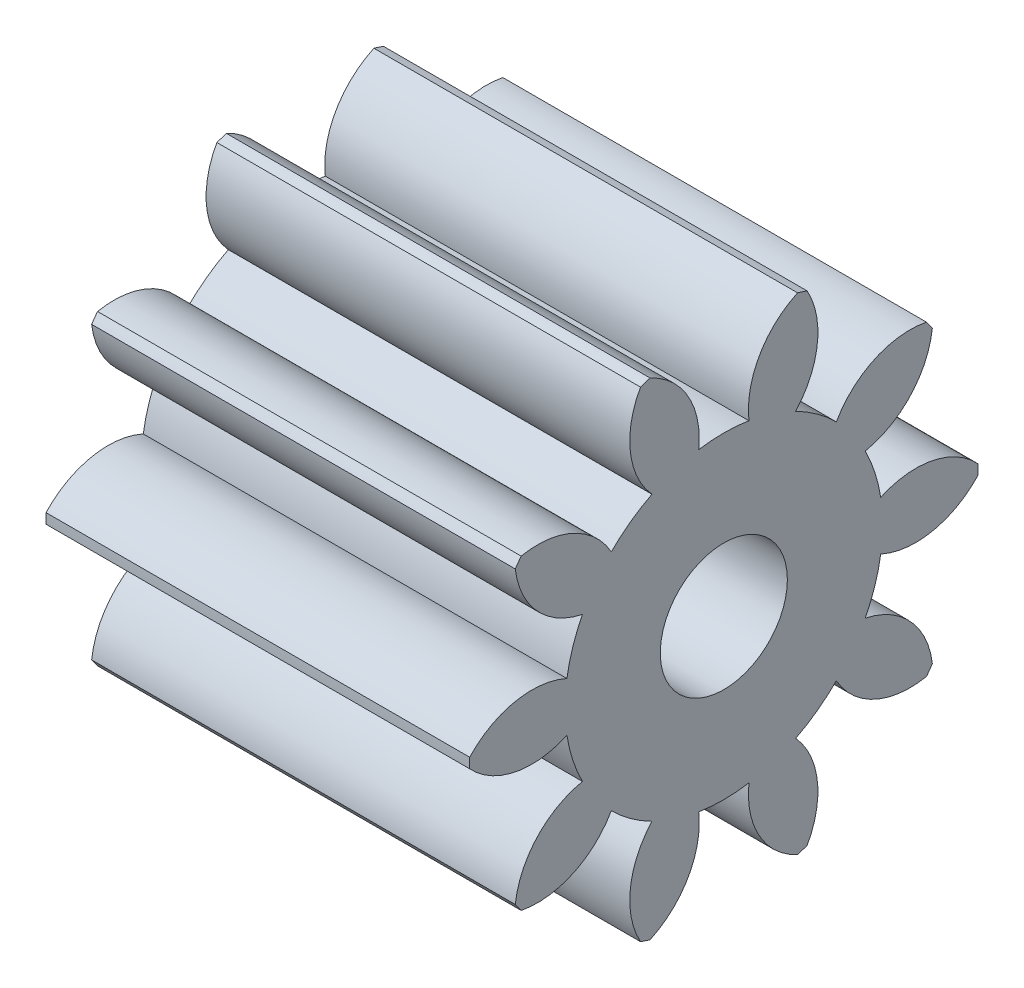
SolidWorks part; units mm, degrees
ref_plane "Plane1" through (0, 0, 0) normal (0, 0, 1) x (1, 0, 0)
ref_plane "Plane2" through (0, 0, 0) normal (0, 1, 0) x (1, 0, 0)
ref_plane "Plane3" through (0, 0, 0) normal (1, 0, 0) x (0, 0, -1)
sketch "HoldingSke" plane through (0, 0, 0) normal (0, 1, 0) x (1, 0, 0)
  line L0 (0, 0) -> (0.9848, -0.1736)
  line L1 (-15, 0) -> (100, 0) construction
  line L2 (0, 0) -> (-2.1039, 2.3779)
  line L3 (0, 0) -> (-11.863, 4.5341)
  line L4 (0, 0) -> (8.5048, 1.4996)
  line L5 (0, 0) -> (-46.8476, -17.4728)
  line L6 (0, 0) -> (-9.9476, -6.7116)
  line L7 (-2.1039, 2.3779) -> (8.6586, 51.2059)
  line L8 (-76.2, 54.61) -> (-76.1, 54.61)
  line L9 (-71.009, 38.7566) -> (-53.1078, 45.2721)
  line L10 (-76.2, 71.12) -> (104.1128, 71.12)
  line L11 (0, 0) -> (-12, 0)
  line L12 (-76.2, 101.6) -> (-76.162, 101.6)
  line L13 (24.9733, 27.94) -> (52.9518, 28.4284)
  line L14 (24.9733, 27.94) -> (24.9743, 27.94)
  line L15 (24.9733, 27.94) -> (100.4006, 29.5858)
  line L16 (-63.627, -1) -> (-12.827, -1)
  circle A0 centre (0, 0) radius 0.4
  circle A1 centre (0, 0) radius 3.749
  circle A2 centre (0, 0) radius 37.5
  circle A3 centre (0, 0) radius 0.4
  dimension "MHD" = 7.498
  dimension "Hub_dia" = 75
  dimension "Bore" = 0.8
  dimension "MBD" = 0.8
  dimension "Num_teeth" = 10
  dimension "Pitch" = 1
  dimension "Overall_len" = 50
  dimension "Show_teeth" = 10
  dimension "Thickness" = 12
  dimension "OAL" = 50.0001
  dimension "T_dim" = 0.1
  dimension "Ap" = 20
  dimension "H" = 19.05
  dimension "Pitch_radius" = 180.3128
  dimension "Width" = 12
  dimension "Backlash" = 0.038
  dimension "Addendum_fac" = 1
  dimension "Dedendum_fac" = 1.25
  dimension "Clearance_fac" = 0.25
  dimension "Dedendum_add" = 0.001
  dimension "Module" = 1
sketch "BasProSke" plane through (0, 0, 0) normal (0, 1, 0) x (1, 0, 0)
  line L0 (-10, 0) -> (60, 0) construction
  line L1 (0, 0) -> (0, 6)
  line L2 (0, 0) -> (10, 0)
  line L3 (10, 0) -> (10, 6)
  line L4 (10, 6) -> (0, 6)
  dimension "Thickness" = 10
  dimension "Diameter" = 12
revolve "Base-Revolve" add sketch "BasProSke" angle 360 about L0
sketch "TooCutSke" plane through (0, 0, 0) normal (1, 0, 0) x (0, 0, -1)
  line L1 (0, 0) -> (0, 107) construction
  line L2 (0, 0) -> (-0.8485, 4.9275) construction
  line L3 (0, 0) -> (-3.0584, 9.4126) construction
  line L4 (-0.8485, 4.9275) -> (-1.5292, 4.7063) construction
  arc A0 (0.5928, 3.7018) -> (-0.5928, 3.7018) centre (0, 0) ccw
  arc A1 (1.7758, 5.7578) -> (-1.7758, 5.7578) centre (0, 0) ccw
  circle A2 centre (0, 0) radius 5 construction
  circle A3 centre (0, 0) radius 4.6985 construction
  arc A4 (-0.5928, 3.7018) -> (-1.7758, 5.7578) centre (-2.5801, 3.9267) ccw
  arc A5 (1.7758, 5.7578) -> (0.5928, 3.7018) centre (2.5801, 3.9267) ccw
  dimension "Root_dia" = 7.498
  dimension "Overcut_dia" = 12.0508
  dimension "Pitch_dia" = 10
  dimension "Base_dia" = 9.3969
  dimension "Flank_rad" = 2
  dimension "Half_ang" = 18
  dimension "Half_CT" = 0.7157
extrude "ToothCut" cut sketch "TooCutSke" along normal through all
fillet "Breaks" [suppressed] radius 0.02
fillet "RootFillets" [suppressed] radius 0.251
pattern_circular "TeethCuts" count 10 every 36 about axis through (-10, 0, 0) along (1, 0, 0) of "ToothCut", "RootFillets", "Breaks"
sketch "HubNeaOneSke" plane through (0, 0, 0) normal (-1, 0, 0) x (0, 0, 1)
  circle A0 centre (0, 0) radius 3.749
  dimension "Diameter" = 7.498
extrude "HubNearOne" [suppressed] add sketch "HubNeaOneSke" along normal blind 40.0001
sketch "HubNeaBotSke" plane through (0, 0, 0) normal (-1, 0, 0) x (0, 0, 1)
  circle A0 centre (0, 0) radius 3.749
  dimension "Diameter" = 7.498
extrude "HubNearBoth" [suppressed] add sketch "HubNeaBotSke" along normal blind 20
ref_plane "FarPln" through (10, 0, 0) normal (1, 0, 0) x (0, 0, -1)
sketch "HubFarSke" plane through (10, 0, 0) normal (1, 0, 0) x (0, 0, -1)
  circle A0 centre (0, 0) radius 3.749
  dimension "Diameter" = 7.498
extrude "HubFar" [suppressed] add sketch "HubFarSke" along normal blind 20
sketch "BorSke" plane through (0, 0, 0) normal (1, 0, 0) x (0, 0, -1)
  circle A0 centre (0, 0) radius 0.4
  dimension "Diameter" = 0.8
extrude "Bore" cut sketch "BorSke" along normal mid plane 100.0001
sketch "KeySke" plane through (0, 0, 0) normal (1, 0, 0) x (0, 0, -1)
  line L0 (-0.05, 0) -> (-0.05, 0.5)
  line L1 (-0.05, 0.5) -> (0.05, 0.5)
  line L2 (0.05, 0.5) -> (0.05, 0)
  line L3 (0, 0) -> (0, 34) construction
  line L4 (-0.05, 0) -> (0.05, 0)
  dimension "Offset" = 0.5
  dimension "Width" = 0.1
extrude "Keyway" [suppressed] cut sketch "KeySke" along normal mid plane 100.0001
pattern_circular "Keyway2" [suppressed] count 2 every 90 about axis through (-10, 0, 0) along (1, 0, 0)
sketch "Sketch1" plane through (10, 0, 0) normal (1, 0, 0) x (0, 0, -1)
  circle A0 centre (0, 0) radius 1.5
  circle A1 centre (0, 0) radius 4.8745 construction
  dimension "D1" = 3
  dimension "D2" = 9.749
extrude "Cut-Extrude1" cut sketch "Sketch1" against normal through all contours A0
sketch "Sketch2" plane through (10, 0, 0) normal (1, 0, 0) x (0, 0, -1)
  circle A0 centre (0, 0) radius 4.8745 construction
  dimension "D1" = 9.749
equation "' \"Module@HoldingSke\" = 6.35"
equation "' \"Num_teeth@HoldingSke\" = 12"
equation "' \"Ap@HoldingSke\" =  20"
equation "' \"Ap@HoldingSke\" = 20"
equation "' \"Width@HoldingSke\" = 0.5 * 25.4"
equation "' \"Hub_dia@HoldingSke\"= 1 * 25.4"
equation "' \"Hub_dia@HoldingSke\" = 1 * 25.4"
equation "' \"Overall_len@HoldingSke\" = 1.0 * 25.4"
equation "' \"Bore@HoldingSke\" = 0.75 * 25.4"
equation "' \"T_dim@HoldingSke\" = 0.1 * 25.4"
equation "' \"Width@KeySke\" = 0.25 * 25.4"
equation "' \"Show_teeth@HoldingSke\" = 13"
equation "' \"Backlash@HoldingSke\" = 0.009 * 25.4"
equation "' \"Addendum_fac@HoldingSke\" = 1.0"
equation "' \"Dedendum_fac@HoldingSke\" = 1.25"
equation "' \"Dedendum_add@HoldingSke\" = 0.00005 * 25.4"
equation "' \"Clearance_fac@HoldingSke\" = 0.25"
equation "\"Pitch@HoldingSke\" = 1 / \"Module@HoldingSke\""
equation "\"Overcut_dia@TooCutSke\" = (\"Num_teeth@HoldingSke\" + 2 * \"Addendum_fac@HoldingSke\") / \"Pitch@HoldingSke\" + 0.002 * 25.4"
equation "\"Pitch_dia@TooCutSke\" = \"Num_teeth@HoldingSke\" / \"Pitch@HoldingSke\""
equation "\"Base_dia@TooCutSke\" = \"Num_teeth@HoldingSke\" / \"Pitch@HoldingSke\" * cos((\"Ap@HoldingSke\"  * 3.14159265 / 180))"
equation "\"Root_dia@TooCutSke\" = (\"Num_teeth@HoldingSke\" + 2) / \"Pitch@HoldingSke\" - 2 * (\"Addendum_fac@HoldingSke\" + \"Dedendum_fac@HoldingSke\") / \"Pitch@HoldingSke\" - \"Dedendum_add@HoldingSke\" * 2"
equation "\"Half_ang@TooCutSke\" = 180 / \"Num_teeth@HoldingSke\""
equation "\"Half_CT@TooCutSke\" = \"Num_teeth@HoldingSke\" / \"Pitch@HoldingSke\" * sin((3.14159265 / 2 / \"Num_teeth@HoldingSke\")) / 2 - 7 * \"Backlash@HoldingSke\" / 4"
equation "\"Flank_rad@TooCutSke\" = \"Num_teeth@HoldingSke\" / \"Pitch@HoldingSke\" / 5"
equation "\"Radius@RootFillets\" = \"Clearance_fac@HoldingSke\" / \"Pitch@HoldingSke\" + \"Dedendum_add@HoldingSke\""
equation "\"Break_rad@Breaks\" = 0.02 / \"Pitch@HoldingSke\""
equation "\"Thickness@HoldingSke\" = \"Width@HoldingSke\""
equation "\"OAL@HoldingSke\" = \"Thickness@HoldingSke\""
equation "\"MHD@HoldingSke\" = (\"Num_teeth@HoldingSke\" + 2) / \"Pitch@HoldingSke\" - 2 * (\"Addendum_fac@HoldingSke\" + \"Dedendum_fac@HoldingSke\")  / \"Pitch@HoldingSke\" - \"Dedendum_add@HoldingSke\" * 2"
equation "\"MBD@HoldingSke\" = (\"Num_teeth@HoldingSke\" + 2) / \"Pitch@HoldingSke\" - 2 * (\"Addendum_fac@HoldingSke\" + \"Dedendum_fac@HoldingSke\")  / \"Pitch@HoldingSke\" - \"Dedendum_add@HoldingSke\" * 2 - 0.002 * 25.4"
equation "\"MHD@HoldingSke\" = ((sgn( \"MHD@HoldingSke\" - \"Hub_dia@HoldingSke\" )-1)*( \"MHD@HoldingSke\" - \"Hub_dia@HoldingSke\" ))/-2+ \"Hub_dia@HoldingSke\""
equation "\"MBD@HoldingSke\" = ((sgn( \"MBD@HoldingSke\" - \"Bore@HoldingSke\" )-1)*( \"MBD@HoldingSke\" - \"Bore@HoldingSke\" ))/-2+ \"Bore@HoldingSke\""
equation "\"OAL@HoldingSke\" = ((sgn( \"OAL@HoldingSke\" - \"Overall_len@HoldingSke\" )+1)*( \"OAL@HoldingSke\" - \"Overall_len@HoldingSke\" ))/2 + \"Overall_len@HoldingSke\" + 0.000002 * 25.4"
equation "\"Num_teeth@TeethCuts\" = int( \"Show_teeth@HoldingSke\" ) + 1"
equation "\"Num_teeth@TeethCuts\" = ((sgn( \"Num_teeth@TeethCuts\" - \"Num_teeth@HoldingSke\" )-1)*( \"Num_teeth@TeethCuts\" - \"Num_teeth@HoldingSke\" ))/-2+ \"Num_teeth@HoldingSke\""
equation "\"Num_teeth@TeethCuts\" = ((sgn( \"Num_teeth@TeethCuts\" - 2.0)+1)*( \"Num_teeth@TeethCuts\" - 2.0))/2 +2.0"
equation "\"Angle@TeethCuts\" = 360.0 / \"Num_teeth@HoldingSke\""
equation "\"Diameter@BasProSke\" = (\"Num_teeth@HoldingSke\" + 2 * \"Addendum_fac@HoldingSke\") / \"Pitch@HoldingSke\""
equation "' \"Fillet_rad@BasProSke\" =  \"Thickness@HoldingSke\" * 0.05"
equation "' \"Fillet_rad@BasProSke\" = \"Thickness@HoldingSke\" * 0.05"
equation "\"MHD@HoldingSke\" = ((sgn( \"MHD@HoldingSke\" - \"Root_dia@TooCutSke\" )-1)*( \"MHD@HoldingSke\" - \"Root_dia@TooCutSke\" ))/-2+ \"Root_dia@TooCutSke\""
equation "\"Diameter@HubNeaOneSke\" = \"MHD@HoldingSke\""
equation "\"Length@HubNearOne\" = \"OAL@HoldingSke\" - \"Thickness@BasProSke\""
equation "\"Diameter@HubNeaBotSke\" = \"MHD@HoldingSke\""
equation "\"Length@HubNearBoth\" = ( \"OAL@HoldingSke\" - \"Thickness@BasProSke\" ) / 2.0"
equation "\"Thickness@FarPln\" = \"Thickness@BasProSke\""
equation "\"Diameter@HubFarSke\" = \"MHD@HoldingSke\""
equation "\"Length@HubFar\" = ( \"OAL@HoldingSke\" - \"Thickness@BasProSke\" ) / 2.0"
equation "\"Diameter@BorSke\" = \"MBD@HoldingSke\""
equation "\"D1@Bore\" = \"OAL@HoldingSke\" * 2.0"
equation "\"D1@Keyway\" = \"OAL@HoldingSke\" * 2.0"
equation "\"Offset@KeySke\" = \"T_dim@HoldingSke\" + \"MBD@HoldingSke\" / 2.0"
